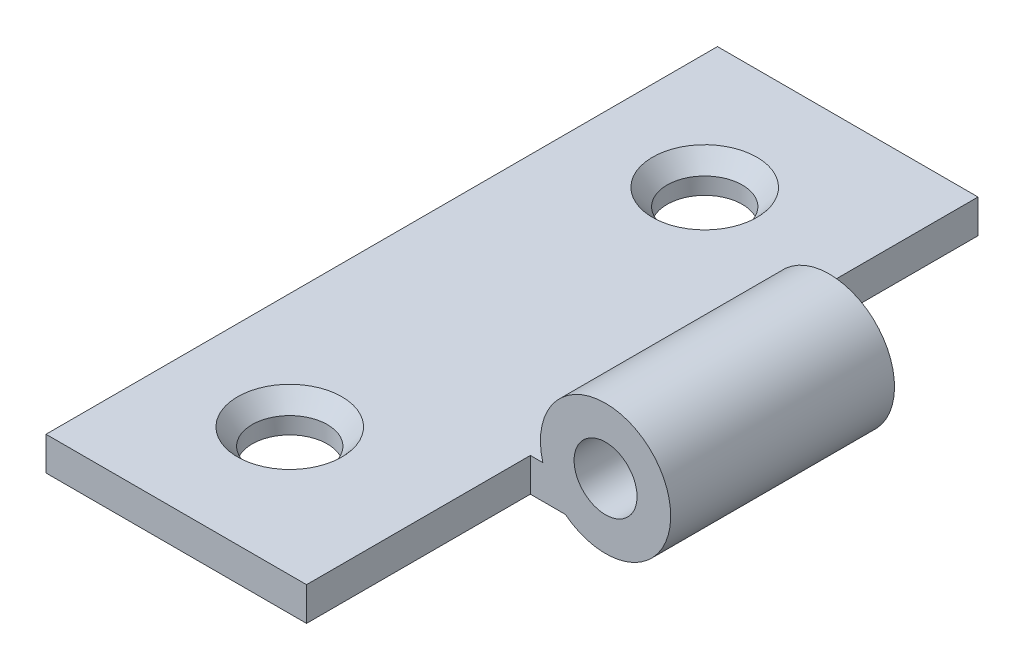
SolidWorks part; units mm, degrees
ref_plane "Front Plane" through (0, 0, 0) normal (0, 0, 1) x (1, 0, 0)
ref_plane "Top Plane" through (0, 0, 0) normal (0, 1, 0) x (1, 0, 0)
ref_plane "Right Plane" through (0, 0, 0) normal (1, 0, 0) x (0, 0, -1)
sketch "Sketch1" plane through (0, 0, 0) normal (0, 0, 1) x (1, 0, 0)
  line L0 (12.7, -2.157) -> (1.1906, -2.157)
  line L1 (12.7, -2.157) -> (12.7, -0.887)
  line L2 (12.7, -0.887) -> (2.2986, -0.887)
  line L3 (1.1906, -2.157) -> (1.1906, 0) construction
  line L4 (-2.4638, 4.06) -> (-2.4638, -1.9388) construction
  line L5 (-12.7, -0.6688) -> (-2.8448, -0.6688)
  line L6 (-12.7, -0.6688) -> (-12.7, -1.9388)
  line L7 (-12.7, -1.9388) -> (-2.8448, -1.9388)
  line L8 (-2.8448, -0.6688) -> (-2.8448, -1.9388)
  line L9 (0, 0) -> (-1.1906, 0) construction
  circle A0 centre (0, 0) radius 1.1906
  arc A1 (1.1906, -2.157) -> (2.2986, -0.887) centre (0, 0) cw
  point P5 (-1.1906, 0)
  dimension "D1" = 1.27
  dimension "Pin Dia" = 2.3813
  dimension "knuckle dia" = 4.9276
  dimension "Leaf thick" = 1.27
  dimension "D3" = 0.381
  dimension "D4" = 12.7
extrude "Extrude1" add sketch "Sketch1" along normal mid plane 25.4
sketch "Sketch2" plane through (0, -0.887, 0) normal (0, 1, 0) x (1, 0, 0)
  line L1 (-2.8448, -7.62) -> (2.8448, -7.62)
  line L2 (-2.8448, -7.62) -> (-2.8448, -12.7)
  line L3 (-2.8448, -12.7) -> (2.8448, -12.7)
  line L4 (2.8448, -7.62) -> (2.8448, -12.7)
  line L5 (-2.8448, -2.54) -> (2.8448, -2.54)
  line L6 (-2.8448, -2.54) -> (-2.8448, 2.54)
  line L7 (-2.8448, 2.54) -> (2.8448, 2.54)
  line L8 (2.8448, -2.54) -> (2.8448, 2.54)
  line L9 (-2.8448, 12.7) -> (2.8448, 12.7)
  line L10 (-2.8448, 12.7) -> (-2.8448, 7.62)
  line L11 (-2.8448, 7.62) -> (2.8448, 7.62)
  line L12 (2.8448, 12.7) -> (2.8448, 7.62)
  line L14 (2.4638, 12.7) -> (-2.4638, 12.7) construction
  line L17 (-2.4638, -12.7) -> (2.4638, -12.7) construction
  line L18 (-2.8448, 0) -> (2.8448, 0) construction
  line L19 (12.7, 12.7) -> (2.2986, 12.7) construction
  line L20 (2.4638, -12.7) -> (2.4638, 12.7) construction
  line L21 (-2.8448, 12.7) -> (-12.7, 12.7) construction
  line L22 (-2.4638, 12.7) -> (-2.4638, -12.7) construction
  dimension "D1" = 5.08
  dimension "D2" = 0.381
  dimension "D3" = 0.381
sketch "Sketch6" plane through (0, 0, 0) normal (0, 1, 0) x (1, 0, 0)
  line L0 (-2.4638, -12.7) -> (-2.4638, -13.2715)
  line L1 (-2.4638, 12.7) -> (-1.1906, 12.7)
  line L2 (-1.1906, -12.7) -> (-2.4638, -12.7)
  line L3 (0, 0) -> (0, 12.7) construction
  line L4 (-2.8448, 12.7) -> (-12.7, 12.7) construction
  line L5 (-2.8448, -12.7) -> (-12.7, -12.7) construction
  line L6 (-2.4638, 13.2715) -> (-2.4638, 12.7)
  line L7 (0, 0) -> (6.3351, 0) construction
  line L10 (-1.1906, -12.7) -> (-1.1906, 12.7)
  line L11 (0, 13.843) -> (0, -13.843)
  arc A0 (-2.4638, 13.2715) -> (0, 13.843) centre (0, 8.2464) cw
  arc A1 (-2.4638, -13.2715) -> (0, -13.843) centre (0, -8.2464) ccw
  circle A2 centre (0, 13.2715) radius 0.5715 construction
  dimension "D2" = 1.143
revolve "Revolve1" add sketch "Sketch6" angle 360 about L11
sketch "Sketch20" plane through (0, -0.6688, 0) normal (0, 1, 0) x (1, 0, 0)
  line L0 (-8.3312, 7.8486) -> (-8.3312, -7.8486) construction
  circle A0 centre (-8.3312, 7.8486) radius 1.4224
  circle A1 centre (-8.3312, -7.8486) radius 1.4224
  point P4 (-8.3312, 0)
  dimension "hole dia" = 2.8448
  dimension "side to side" = 8.3312
  dimension "top to bottom" = 15.6972
extrude "Extrude24" cut sketch "Sketch20" against normal through all
chamfer "Chamfer2" distance 0.635 angle 41 2 edges at (-8.3312, -0.6688, 9.271) (-8.3312, -0.6688, -6.4262)
mirror "Mirror2" about plane through (0, 0, 0) normal (1, 0, 0) of "Chamfer2", "Extrude24"
sketch "Sketch23" [suppressed] plane through (0, -1.376, 0) normal (0, 1, 0) x (1, 0, 0)
  line L0 (-19.4564, 0) -> (0, 0) construction
  circle A0 centre (-19.4564, 0) radius 1.7526
  circle A1 centre (-16.637, 29.718) radius 1.7526 construction
  dimension "side to side B" = 19.05
extrude "Extrude25" [suppressed] cut sketch "Sketch23" against normal through all
chamfer "Chamfer3" [suppressed] distance 0.635 angle 41
mirror "Mirror3" [suppressed] about plane through (0, 0, 0) normal (1, 0, 0)
sketch "Sketch8" plane through (0, 0, 0) normal (0, 1, 0) x (1, 0, 0)
  line L0 (-2.8448, 0) -> (2.8448, 0) construction
  line L1 (-2.8448, 4.2333) -> (2.8448, 4.2333)
  line L2 (-2.8448, 4.2333) -> (-2.8448, -4.2333)
  line L3 (-2.8448, -4.2333) -> (2.8448, -4.2333)
  line L4 (2.8448, 4.2333) -> (2.8448, -4.2333)
  line L5 (-2.8448, -12.7) -> (-2.8448, 12.7) construction
  line L6 (0, 4.2333) -> (0, 12.7) construction
  line L7 (2.4638, 12.7) -> (-2.4638, 12.7) construction
extrude "Extrude4" cut sketch "Sketch8" against normal through all and the other way through all
sketch "Sketch9" plane through (0, 0, -4.2333) normal (0, 0, 1) x (1, 0, 0)
  line L0 (-2.3713, -0.6688) -> (-2.8448, -0.6688)
  line L1 (-2.8448, -0.6688) -> (-2.8448, -1.9388)
  line L2 (-2.8448, -1.9388) -> (-1.5203, -1.9388)
  line L3 (-2.8448, -1.9388) -> (-2.8448, -0.6688) construction
  line L4 (-2.8448, -0.6688) -> (-12.7, -0.6688) construction
  line L5 (-12.7, -1.9388) -> (-2.8448, -1.9388) construction
  arc A0 (2.2986, -0.887) -> (1.1906, -2.157) centre (0, 0) ccw construction
  circle A1 centre (0, 0) radius 1.1906 construction
  arc A2 (-1.5203, -1.9388) -> (-2.3713, -0.6688) centre (0, 0) ccw
  circle A3 centre (0, 0) radius 1.1906
extrude "Extrude5" add sketch "Sketch9" along normal up to surface (8.4667 mm away)
sketch "Sketch3" [suppressed] plane through (0, 0, 0) normal (0, 1, 0) x (1, 0, 0)
  line L0 (0, 7.62) -> (0, -7.62) construction
  line L1 (-3.937, 22.86) -> (3.937, 22.86)
  line L2 (-3.937, 22.86) -> (-3.937, 7.62)
  line L3 (-3.937, 7.62) -> (3.937, 7.62)
  line L4 (3.937, 22.86) -> (3.937, 7.62)
  line L5 (-3.937, -7.62) -> (3.937, -7.62)
  line L6 (-3.937, -7.62) -> (-3.937, -22.86)
  line L7 (-3.937, -22.86) -> (3.937, -22.86)
  line L8 (3.937, -7.62) -> (3.937, -22.86)
  line L9 (0, 22.86) -> (0, 38.1) construction
  line L11 (0, -22.86) -> (0, -38.1) construction
  line L13 (-3.937, -38.1) -> (-3.937, 38.1) construction
  line L14 (3.556, 38.1) -> (-3.556, 38.1) construction
extrude "Cut-Extrude1" [suppressed] cut sketch "Sketch3" against normal mid plane 76.2
sketch "Sketch4" [suppressed] plane through (0, 0, -22.86) normal (0, 0, 1) x (1, 0, 0)
  line L0 (-25.4, -2.9508) -> (-3.937, -2.9508) construction
  line L2 (-3.937, -1.376) -> (-3.279, -1.376)
  line L3 (-3.937, -1.376) -> (-3.937, -2.9508)
  line L4 (-3.937, -2.9508) -> (-1.9844, -2.9508)
  circle A0 centre (0, 0) radius 1.9844 construction
  circle A1 centre (0, 0) radius 1.9844
  arc A2 (3.279, -1.376) -> (1.9844, -2.9508) centre (0, 0) ccw construction
  arc A3 (-1.9844, -2.9508) -> (-3.279, -1.376) centre (0, 0) ccw
extrude "Extrude2" [suppressed] add sketch "Sketch4" along normal up to vertex
sketch "Sketch5" [suppressed] plane through (0, 0, 7.62) normal (0, 0, 1) x (1, 0, 0)
  line L3 (-3.279, -1.376) -> (-3.937, -1.376)
  line L4 (-3.937, -2.9508) -> (-1.9844, -2.9508)
  line L5 (-3.937, -1.376) -> (-3.937, -2.9508)
  line L6 (-3.279, -1.376) -> (-3.937, -1.376)
  line L7 (-3.937, -2.9508) -> (-1.9844, -2.9508)
  line L8 (-3.937, -1.376) -> (-3.937, -2.9508)
  circle A1 centre (0, 0) radius 1.9844
  circle A2 centre (0, 0) radius 1.9844
  arc A3 (-1.9844, -2.9508) -> (-3.279, -1.376) centre (0, 0) ccw
  arc A4 (-1.9844, -2.9508) -> (-3.279, -1.376) centre (0, 0) ccw
  dimension "D1" = 0
  dimension "D2" = 0
extrude "Extrude3" [suppressed] add sketch "Sketch5" along normal up to vertex
sketch "Sketch19" [suppressed] plane through (0, 0, 0) normal (0, 1, 0) x (1, 0, 0)
  line L1 (-12.7, -12.7) -> (12.7, -12.7)
  line L2 (-12.7, -12.7) -> (-12.7, -13.843)
  line L3 (-12.7, -13.843) -> (12.7, -13.843)
  line L4 (12.7, -12.7) -> (12.7, -13.843)
extrude "Extrude23" [suppressed] cut sketch "Sketch19" against normal through all and the other way through all
chamfer "Chamfer1" [suppressed] distance 0.5953 angle 45
sketch "Sketch21" plane through (0, 0, 0) normal (0, 1, 0) x (1, 0, 0)
  line L0 (-12.7, -12.7) -> (12.7, -12.7) construction
  point P4 (0, -12.7)
delete or keep bodies "Body-Delete/Keep 3" type delete bodies bodies 107
delete or keep bodies "Body-Delete/Keep 6" type delete bodies bodies 109
equation "\"D1@Sketch2\" = \"Leaf Ht@Extrude1\"/5"
equation "\"D4@Sketch1\" = \"Wd@Sketch1\"/2"
equation "\"D2@Sketch6\" = \"Leaf thick@Sketch1\"*.9"
equation "\"D1@Chamfer1\" = \"Pin Dia@Sketch1\" * .25"
equation "\"D1@Chamfer2\" = \"Leaf thick@Sketch1\" * .5"
equation "\"D1@Chamfer3\" = \"D1@Chamfer2\""
equation "\"D2@Chamfer3\" = \"D2@Chamfer2\""
